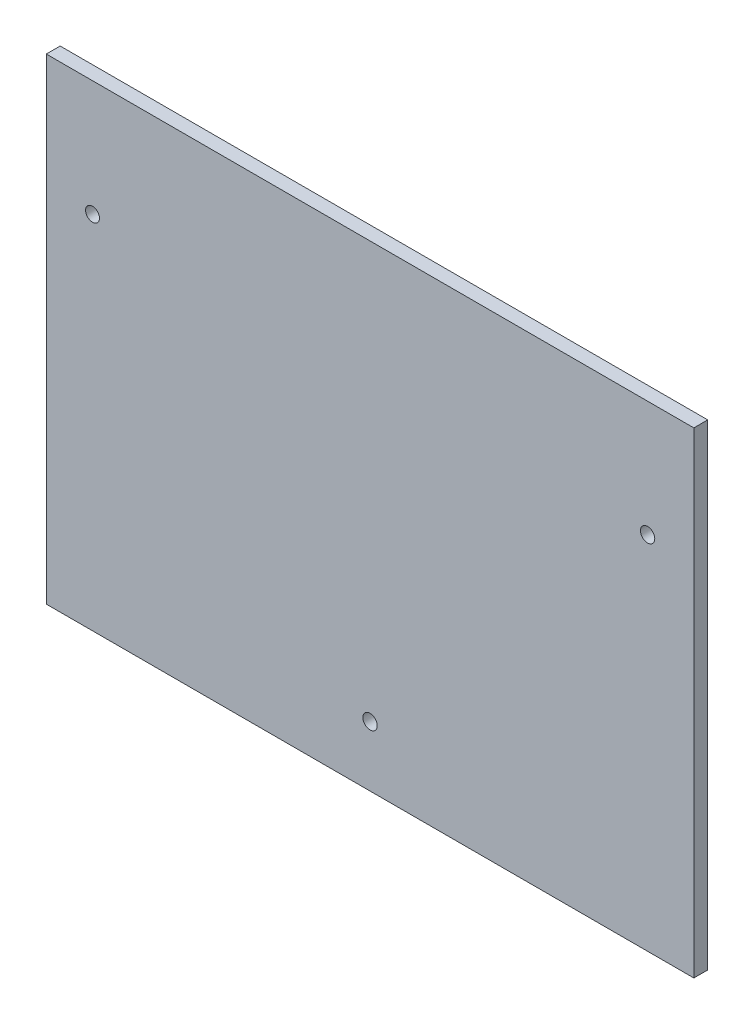
SolidWorks part; units mm, degrees
ref_plane "前视基准面" through (0, 0, 0) normal (0, 0, 1) x (1, 0, 0)
ref_plane "上视基准面" through (0, 0, 0) normal (0, 1, 0) x (1, 0, 0)
ref_plane "右视基准面" through (0, 0, 0) normal (1, 0, 0) x (0, 0, -1)
other "Configuration Table"
sketch "草图1" plane through (0, 0, 0) normal (0, 0, 1) x (1, 0, 0)
  line L1 (70, -51.5) -> (-70, -51.5)
  line L2 (70, -51.5) -> (70, 51.5)
  line L3 (70, 51.5) -> (-70, 51.5)
  line L4 (-70, -51.5) -> (-70, 51.5)
  line L5 (70, -51.5) -> (-70, 51.5) construction
  line L6 (70, 51.5) -> (-70, -51.5) construction
  point P0 (0, 0)
  dimension "D1" = 103
  dimension "D2" = 140
extrude "凸台-拉伸1" add sketch "草图1" along normal blind 3
sketch "草图2" plane through (0, 0, 3) normal (0, 0, 1) x (1, 0, 0)
  circle A0 centre (-60, 26.5) radius 1.5
  circle A1 centre (60, 26.5) radius 1.55
  circle A2 centre (0, -38.5) radius 1.55
extrude "切除-拉伸1" cut sketch "草图2" against normal through all
